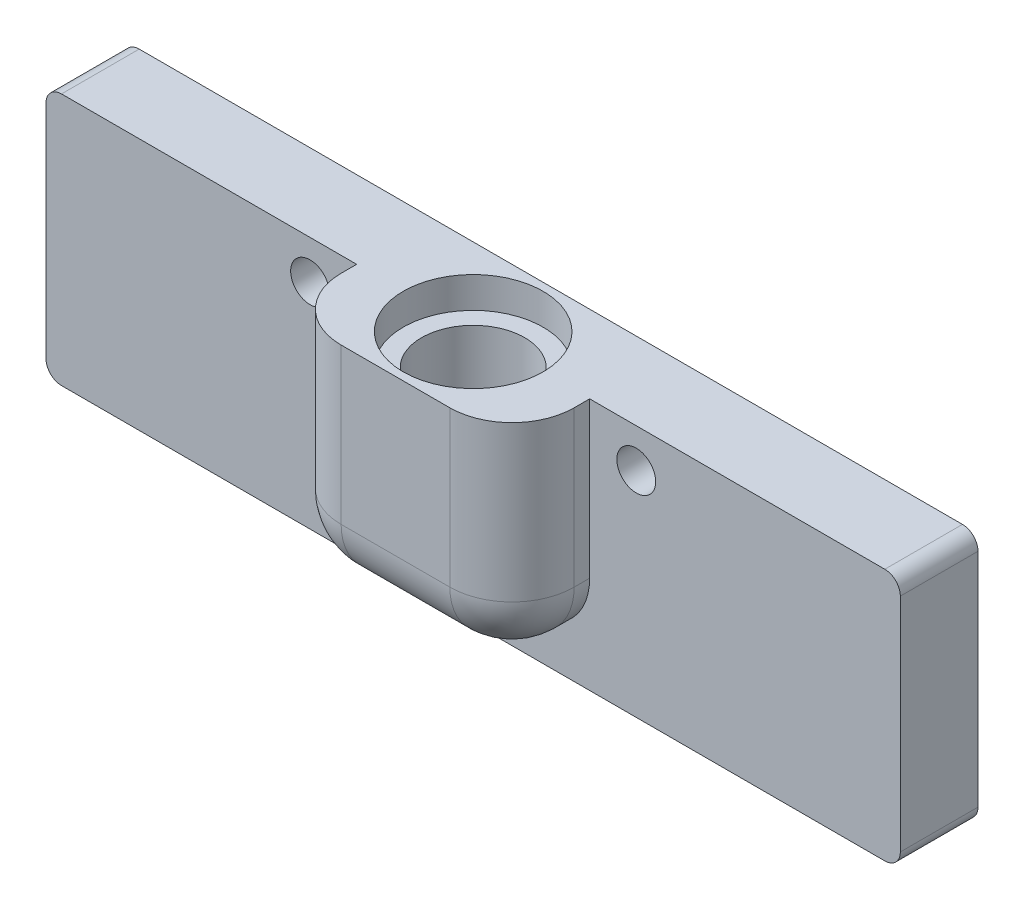
SolidWorks part; units mm, degrees
ref_plane "Front Plane" through (0, 0, 0) normal (0, 0, 1) x (1, 0, 0)
ref_plane "Top Plane" through (0, 0, 0) normal (0, 1, 0) x (1, 0, 0)
ref_plane "Right Plane" through (0, 0, 0) normal (1, 0, 0) x (0, 0, -1)
ref_plane "Plane1" through (0, 0, 0) normal (0, 0, -1) x (-1, 0, 0)
sketch "Sketch1" plane through (0, 0, 0) normal (0, 0, -1) x (-1, 0, 0)
  line L0 (27.5, -16.2631) -> (27.5, 0)
  line L1 (27.5, 0) -> (-27.5, 0)
  line L2 (-27.5, 0) -> (-27.5, -16.2631)
  line L3 (27.5, -16.2631) -> (-27.5, -16.2631)
extrude "Boss-Extrude1" add sketch "Sketch1" against normal blind 5
sketch "Sketch4" plane through (0, 0, 5) normal (0, 0, 1) x (1, 0, 0)
  line L0 (7.5, 0) -> (7.5, -14)
  line L1 (7.5, -14) -> (-7.5, -14)
  line L2 (-7.5, -14) -> (-7.5, 0)
  line L3 (-7.5, 0) -> (7.5, 0)
extrude "Boss-Extrude2" add sketch "Sketch4" along normal blind 5
hole_wizard "CBORE for M6 Hex Head Bolt1" positions "Sketch6" profile "Sketch5" counterbore size "M6" standard "ANSI Metric"
sketch "Sketch6" plane through (0, 0, 0) normal (0, 1, 0) x (1, 0, 0)
  point P0 (0, -5)
sketch "Sketch5" plane through (0, 0, 5) normal (1, 0, 0) x (0, 0, 1)
  line L0 (0, 0) -> (0, 11.997)
  line L1 (0, 11.997) -> (3.3235, 10)
  line L2 (3.3235, 10) -> (3.3235, 2)
  line L3 (3.3235, 2) -> (4.5, 2)
  line L4 (4.5, 2) -> (4.5, 0)
  line L5 (4.5, 0) -> (0, 0)
  line L10 (0, 11.997) -> (-3.3235, 10) construction
  line L11 (0, -6.35) -> (0, 107.95) construction
  dimension "Hole Dia." = 6.647
  dimension "Hole Depth" = 10
  dimension "C'Bore Dia." = 9
  dimension "C'Bore Depth" = 2
  dimension "Drill Angle" = 118
fillet "Fillet1" radius 1 4 edges at (27.5, 0, 2.5) (-27.5, 0, 2.5) (27.5, -16.2631, 2.5) (-27.5, -16.2631, 2.5)
fillet "Fillet2" radius 4 5 edges at (7.5, -14, 7.5) (7.5, -7, 10) (-7.5, -14, 7.5) (0, -14, 10) (-7.5, -7, 10)
hole_wizard "Tap Drill for M3x0.5 Tap1" positions "3DSketch1" profile "Sketch7" hole size "M3x0.5" standard "ANSI Metric" end condition through all
sketch3d "3DSketch1"
  line L0 (-7.5, 0, 5) -> (-7.5, -10, 5) construction
  line L1 (7.5, -10, 5) -> (7.5, 0, 5) construction
  line L2 (-26.5, 0, 5) -> (-7.5, 0, 5) construction
  point P0 (-10.5, -2.5, 5)
  point P2 (10.5, -2.5, 5)
  dimension "D1" = 3
  dimension "D2" = 3
  dimension "D3" = 2.5
sketch "Sketch7" plane through (-10.5, -2.5, 5) normal (1, 0, 0) x (0, -1, 0)
  line L0 (0, 0) -> (0, 5)
  line L1 (0, 5) -> (1.25, 5)
  line L2 (1.25, 5) -> (1.25, 0)
  line L5 (1.25, 0) -> (0, 0)
  line L11 (0, -6.35) -> (0, 107.95) construction
  dimension "Thru Hole Dia." = 2.5
  dimension "Thru Hole Depth" = 5
